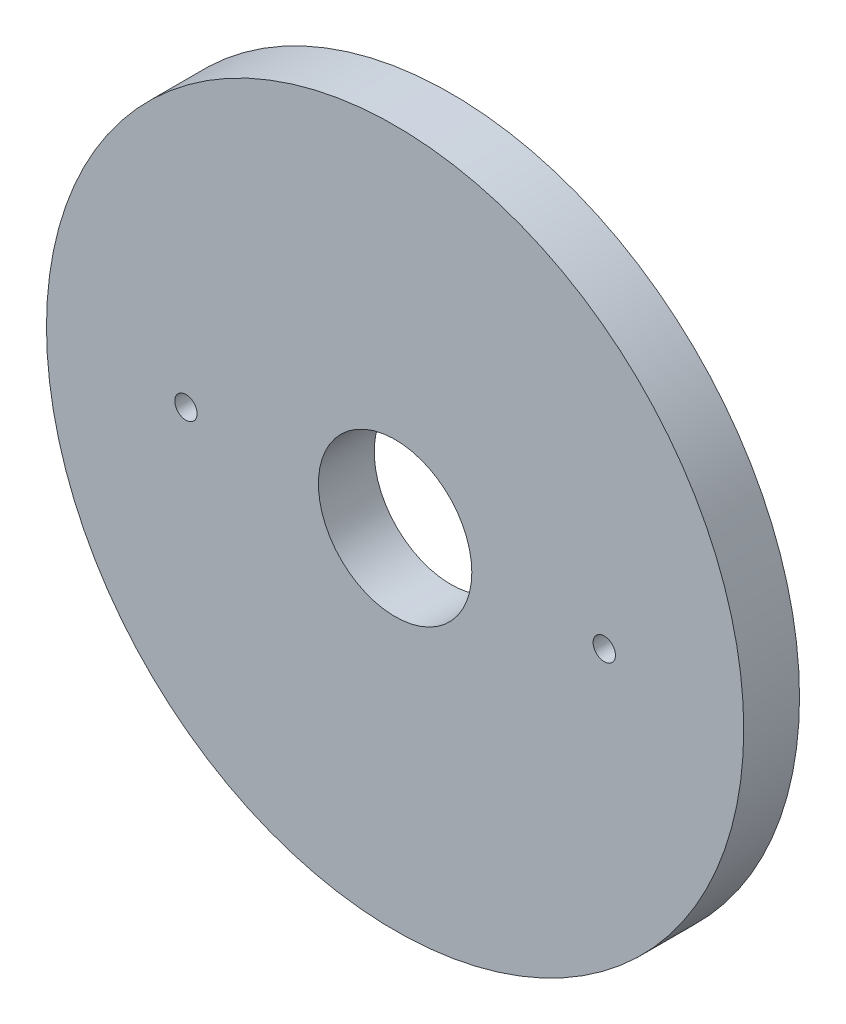
SolidWorks part; units mm, degrees
ref_plane "Plan de face" through (0, 0, 0) normal (0, 0, 1) x (1, 0, 0)
ref_plane "Plan de dessus" through (0, 0, 0) normal (0, 1, 0) x (1, 0, 0)
ref_plane "Plan de droite" through (0, 0, 0) normal (1, 0, 0) x (0, 0, -1)
sketch "Esquisse1" plane through (0, 0, 0) normal (0, 0, 1) x (1, 0, 0)
  circle A0 centre (0, 0) radius 50
  circle A1 centre (0, 0) radius 11
  dimension "D1" = 100
  dimension "D2" = 22
extrude "Boss.-Extru.1" add sketch "Esquisse1" along normal blind 8
sketch "Esquisse2" plane through (0, 0, 0) normal (0, 0, -1) x (-1, 0, 0)
  circle A0 centre (30, 0) radius 1.6
  circle A1 centre (-30, 0) radius 1.6
  dimension "D1" = 30
  dimension "D2" = 3.2
  dimension "D3" = 3.2
  dimension "D4" = 30
extrude "Enlèv. mat.-Extru.1" cut sketch "Esquisse2" against normal through all
sketch "Esquisse3" plane through (0, 0, 0) normal (0, 0, -1) x (-1, 0, 0)
  circle A0 centre (30, 0) radius 2.85
  circle A1 centre (-30, 0) radius 2.85
  dimension "D1" = 5.7
  dimension "D2" = 5.7
extrude "Enlèv. mat.-Extru.2" cut sketch "Esquisse3" against normal blind 3
